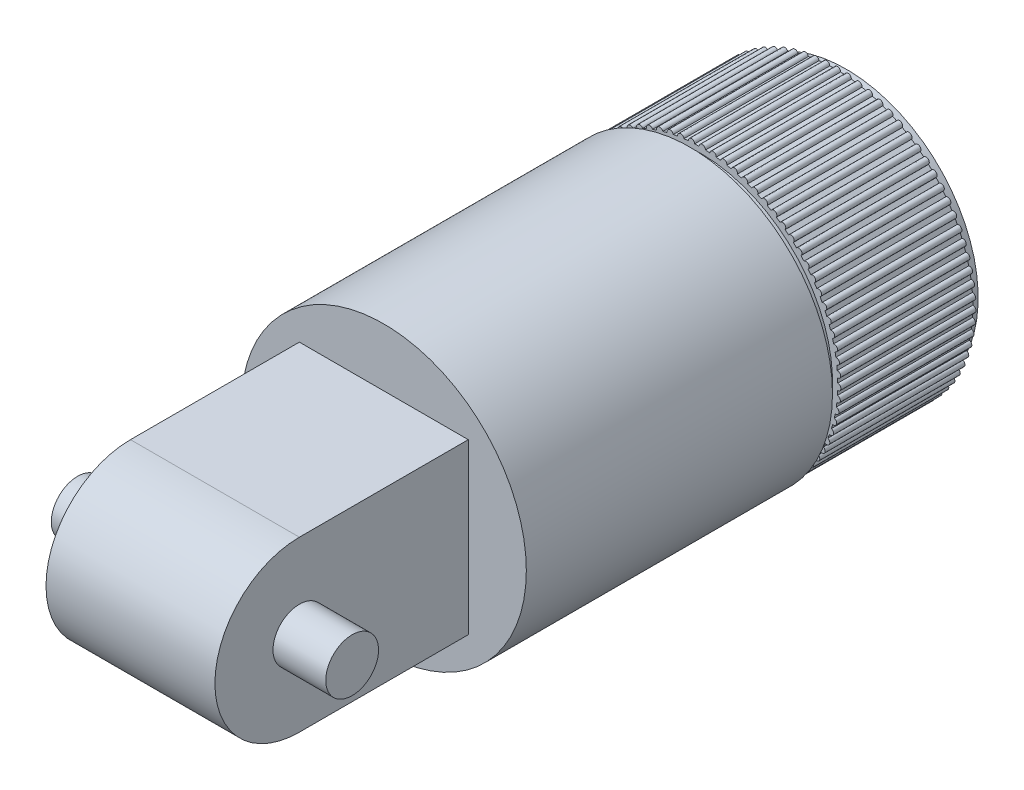
SolidWorks part; units mm, degrees
ref_plane "Front Plane" through (0, 0, 0) normal (0, 0, 1) x (1, 0, 0)
ref_plane "Top Plane" through (0, 0, 0) normal (0, 1, 0) x (1, 0, 0)
ref_plane "Right Plane" through (0, 0, 0) normal (1, 0, 0) x (0, 0, -1)
sketch "Sketch1" plane through (0, 0, 0) normal (0, 0, 1) x (1, 0, 0)
  circle A0 centre (0, 0) radius 3
  circle A1 centre (0, 0) radius 6.5
  arc A2 (0.2338, 6.4958) -> (-0.0661, 6.4997) centre (0.0839, 6.4995) ccw
  arc A3 (0.7428, 6.4574) -> (0.444, 6.4848) centre (0.5936, 6.4728) ccw
  arc A4 (1.2471, 6.3792) -> (0.9515, 6.43) centre (1.0996, 6.4063) ccw
  arc A5 (1.7438, 6.2617) -> (1.453, 6.3355) centre (1.5988, 6.3003) ccw
  arc A6 (2.2297, 6.1056) -> (1.9456, 6.202) centre (2.0882, 6.1554) ccw
  arc A7 (2.7019, 5.9118) -> (2.4262, 6.0302) centre (2.5647, 5.9726) ccw
  arc A8 (3.1574, 5.6816) -> (2.8919, 5.8213) centre (3.0254, 5.753) ccw
  arc A9 (3.5934, 5.4164) -> (3.3397, 5.5764) centre (3.4675, 5.4979) ccw
  arc A10 (4.0073, 5.1178) -> (3.7669, 5.2972) centre (3.8881, 5.2089) ccw
  arc A11 (4.3965, 4.7876) -> (4.1709, 4.9853) centre (4.2848, 4.8878) ccw
  arc A12 (4.7586, 4.4279) -> (4.5492, 4.6427) centre (4.6551, 4.5365) ccw
  arc A13 (5.0913, 4.0409) -> (4.8994, 4.2715) centre (4.9967, 4.1573) ccw
  arc A14 (5.3927, 3.629) -> (5.2195, 3.8739) centre (5.3075, 3.7524) ccw
  arc A15 (5.6608, 3.1947) -> (5.5073, 3.4524) centre (5.5855, 3.3244) ccw
  arc A16 (5.894, 2.7407) -> (5.7612, 3.0097) centre (5.8291, 2.876) ccw
  arc A17 (6.0908, 2.2698) -> (5.9796, 2.5484) centre (6.0368, 2.4097) ccw
  arc A18 (6.2501, 1.7849) -> (6.1611, 2.0714) centre (6.2073, 1.9287) ccw
  arc A19 (6.3709, 1.289) -> (6.3046, 1.5816) centre (6.3395, 1.4357) ccw
  arc A20 (6.4524, 0.7852) -> (6.4093, 1.0821) centre (6.4326, 0.9339) ccw
  arc A21 (6.4941, 0.2765) -> (6.4744, 0.5759) centre (6.486, 0.4263) ccw
  arc A22 (6.4958, -0.2338) -> (6.4997, 0.0661) centre (6.4995, -0.0839) ccw
  arc A23 (6.4574, -0.7428) -> (6.4848, -0.444) centre (6.4728, -0.5936) ccw
  arc A24 (6.3792, -1.2471) -> (6.43, -0.9515) centre (6.4063, -1.0996) ccw
  arc A25 (6.2617, -1.7438) -> (6.3355, -1.453) centre (6.3003, -1.5988) ccw
  arc A26 (6.1056, -2.2297) -> (6.202, -1.9456) centre (6.1554, -2.0882) ccw
  arc A27 (5.9118, -2.7019) -> (6.0302, -2.4262) centre (5.9726, -2.5647) ccw
  arc A28 (5.6816, -3.1574) -> (5.8213, -2.8919) centre (5.753, -3.0254) ccw
  arc A29 (5.4164, -3.5934) -> (5.5764, -3.3397) centre (5.4979, -3.4675) ccw
  arc A30 (5.1178, -4.0073) -> (5.2972, -3.7669) centre (5.2089, -3.8881) ccw
  arc A31 (4.7876, -4.3965) -> (4.9853, -4.1709) centre (4.8878, -4.2848) ccw
  arc A32 (4.4279, -4.7586) -> (4.6427, -4.5492) centre (4.5365, -4.6551) ccw
  arc A33 (4.0409, -5.0913) -> (4.2715, -4.8994) centre (4.1573, -4.9967) ccw
  arc A34 (3.629, -5.3927) -> (3.8739, -5.2195) centre (3.7524, -5.3075) ccw
  arc A35 (3.1947, -5.6608) -> (3.4524, -5.5073) centre (3.3244, -5.5855) ccw
  arc A36 (2.7407, -5.894) -> (3.0097, -5.7612) centre (2.876, -5.8291) ccw
  arc A37 (2.2698, -6.0908) -> (2.5484, -5.9796) centre (2.4097, -6.0368) ccw
  arc A38 (1.7849, -6.2501) -> (2.0714, -6.1611) centre (1.9287, -6.2073) ccw
  arc A39 (1.289, -6.3709) -> (1.5816, -6.3046) centre (1.4357, -6.3395) ccw
  arc A40 (0.7852, -6.4524) -> (1.0821, -6.4093) centre (0.9339, -6.4326) ccw
  arc A41 (0.2765, -6.4941) -> (0.5759, -6.4744) centre (0.4263, -6.486) ccw
  arc A42 (-0.2338, -6.4958) -> (0.0661, -6.4997) centre (-0.0839, -6.4995) ccw
  arc A43 (-0.7428, -6.4574) -> (-0.444, -6.4848) centre (-0.5936, -6.4728) ccw
  arc A44 (-1.2471, -6.3792) -> (-0.9515, -6.43) centre (-1.0996, -6.4063) ccw
  arc A45 (-1.7438, -6.2617) -> (-1.453, -6.3355) centre (-1.5988, -6.3003) ccw
  arc A46 (-2.2297, -6.1056) -> (-1.9456, -6.202) centre (-2.0882, -6.1554) ccw
  arc A47 (-2.7019, -5.9118) -> (-2.4262, -6.0302) centre (-2.5647, -5.9726) ccw
  arc A48 (-3.1574, -5.6816) -> (-2.8919, -5.8213) centre (-3.0254, -5.753) ccw
  arc A49 (-3.5934, -5.4164) -> (-3.3397, -5.5764) centre (-3.4675, -5.4979) ccw
  arc A50 (-4.0073, -5.1178) -> (-3.7669, -5.2972) centre (-3.8881, -5.2089) ccw
  arc A51 (-4.3965, -4.7876) -> (-4.1709, -4.9853) centre (-4.2848, -4.8878) ccw
  arc A52 (-4.7586, -4.4279) -> (-4.5492, -4.6427) centre (-4.6551, -4.5365) ccw
  arc A53 (-5.0913, -4.0409) -> (-4.8994, -4.2715) centre (-4.9967, -4.1573) ccw
  arc A54 (-5.3927, -3.629) -> (-5.2195, -3.8739) centre (-5.3075, -3.7524) ccw
  arc A55 (-5.6608, -3.1947) -> (-5.5073, -3.4524) centre (-5.5855, -3.3244) ccw
  arc A56 (-5.894, -2.7407) -> (-5.7612, -3.0097) centre (-5.8291, -2.876) ccw
  arc A57 (-6.0908, -2.2698) -> (-5.9796, -2.5484) centre (-6.0368, -2.4097) ccw
  arc A58 (-6.2501, -1.7849) -> (-6.1611, -2.0714) centre (-6.2073, -1.9287) ccw
  arc A59 (-6.3709, -1.289) -> (-6.3046, -1.5816) centre (-6.3395, -1.4357) ccw
  arc A60 (-6.4524, -0.7852) -> (-6.4093, -1.0821) centre (-6.4326, -0.9339) ccw
  arc A61 (-6.4941, -0.2765) -> (-6.4744, -0.5759) centre (-6.486, -0.4263) ccw
  arc A62 (-6.4958, 0.2338) -> (-6.4997, -0.0661) centre (-6.4995, 0.0839) ccw
  arc A63 (-6.4574, 0.7428) -> (-6.4848, 0.444) centre (-6.4728, 0.5936) ccw
  arc A64 (-6.3792, 1.2471) -> (-6.43, 0.9515) centre (-6.4063, 1.0996) ccw
  arc A65 (-6.2617, 1.7438) -> (-6.3355, 1.453) centre (-6.3003, 1.5988) ccw
  arc A66 (-6.1056, 2.2297) -> (-6.202, 1.9456) centre (-6.1554, 2.0882) ccw
  arc A67 (-5.9118, 2.7019) -> (-6.0302, 2.4262) centre (-5.9726, 2.5647) ccw
  arc A68 (-5.6816, 3.1574) -> (-5.8213, 2.8919) centre (-5.753, 3.0254) ccw
  arc A69 (-5.4164, 3.5934) -> (-5.5764, 3.3397) centre (-5.4979, 3.4675) ccw
  arc A70 (-5.1178, 4.0073) -> (-5.2972, 3.7669) centre (-5.2089, 3.8881) ccw
  arc A71 (-4.7876, 4.3965) -> (-4.9853, 4.1709) centre (-4.8878, 4.2848) ccw
  arc A72 (-4.4279, 4.7586) -> (-4.6427, 4.5492) centre (-4.5365, 4.6551) ccw
  arc A73 (-4.0409, 5.0913) -> (-4.2715, 4.8994) centre (-4.1573, 4.9967) ccw
  arc A74 (-3.629, 5.3927) -> (-3.8739, 5.2195) centre (-3.7524, 5.3075) ccw
  arc A75 (-3.1947, 5.6608) -> (-3.4524, 5.5073) centre (-3.3244, 5.5855) ccw
  arc A76 (-2.7407, 5.894) -> (-3.0097, 5.7612) centre (-2.876, 5.8291) ccw
  arc A77 (-2.2698, 6.0908) -> (-2.5484, 5.9796) centre (-2.4097, 6.0368) ccw
  arc A78 (-1.7849, 6.2501) -> (-2.0714, 6.1611) centre (-1.9287, 6.2073) ccw
  arc A79 (-1.289, 6.3709) -> (-1.5816, 6.3046) centre (-1.4357, 6.3395) ccw
  arc A80 (-0.7852, 6.4524) -> (-1.0821, 6.4093) centre (-0.9339, 6.4326) ccw
  arc A81 (-0.2765, 6.4941) -> (-0.5759, 6.4744) centre (-0.4263, 6.486) ccw
  point P5 (0, 0)
  point P8 (0, 0)
  dimension "D1" = 6
  dimension "D2" = 13
  dimension "D3" = 0.3
  dimension "D4" = 80
extrude "Boss-Extrude1" add sketch "Sketch1" along normal blind 6.4 contours A1 | A1 A77 | A1 A76 | A1 A75 | A1 A74 | A1 A73 | A1 A72 | A1 A71 | A1 A70 | A1 A69 | A1 A68 | A1 A67 | A1 A66 | A1 A65 | A1 A64 | A1 A63 | A1 A62 | A1 A61 | A1 A60 | A1 A59 | A1 A58 | A1 A57 | A1 A56 | A1 A55 | A1 A54 | A1 A53 | A1 A52 | A1 A51 | A1 A49 | A1 A50 | A1 A48 | A1 A47 | A1 A46 | A1 A44 | A1 A45 | A1 A43 | A1 A42 | A1 A41 | A1 A40 | A1 A39 | A1 A38 | A1 A37 | A1 A36 | A1 A35 | A1 A34 | A1 A33 | A1 A32 | A1 A31 | A1 A30 | A1 A29 | A1 A28 | A1 A27 | A1 A26 | A1 A25 | A1 A24 | A1 A23 | A1 A22 | A1 A21 | A1 A20 | A1 A19 | A1 A18 | A1 A17 | A1 A16 | A1 A15 | A1 A14 | A1 A13 | A1 A12 | A1 A11 | A1 A10 | A1 A9 | A1 A8 | A1 A7 | A1 A6 | A1 A5 | A1 A4 | A1 A3 | A1 A2 | A1 A81 | A1 A80 | A1 A79 | A1 A78
sketch "Sketch2" plane through (0, 0, 0) normal (0, 0, -1) x (-1, 0, 0)
  circle A0 centre (0, 0) radius 3 construction
  circle A1 centre (0, 0) radius 3
  circle A2 centre (0, 0) radius 6.25
  dimension "D1" = 12.5
extrude "Boss-Extrude2" add sketch "Sketch2" along normal blind 0.5 and the other way blind 6.9
sketch "Sketch4" plane through (0, 0, 6.9) normal (0, 0, 1) x (1, 0, 0)
  circle A0 centre (0, 0) radius 6.75
  dimension "D1" = 13.5
extrude "Boss-Extrude4" add sketch "Sketch4" along normal blind 14.5
sketch "Sketch5" plane through (0, 0, 21.4) normal (0, 0, 1) x (1, 0, 0)
  line L1 (4, -4) -> (-4, -4)
  line L2 (4, -4) -> (4, 4)
  line L3 (4, 4) -> (-4, 4)
  line L4 (-4, -4) -> (-4, 4)
  line L5 (4, -4) -> (-4, 4) construction
  line L6 (4, 4) -> (-4, -4) construction
  point P0 (0, 0)
  dimension "D1" = 8
  dimension "D2" = 8
extrude "Boss-Extrude5" add sketch "Sketch5" along normal blind 8
sketch "Sketch6" plane through (-4, 0, 0) normal (-1, 0, 0) x (0, 0, 1)
  line L0 (29.4, 4) -> (29.4, -4) construction
  line L1 (29.4, 4) -> (29.4, -4)
  arc A0 (29.4, -4) -> (29.4, 4) centre (29.4, 0) ccw
extrude "Boss-Extrude6" add sketch "Sketch6" against normal blind 8
sketch "Sketch8" plane through (0, 0, 0) normal (1, 0, 0) x (0, 0, -1)
  arc A0 (-29.4, 4) -> (-29.4, -4) centre (-29.4, 0) ccw construction
  arc A1 (-29.4, 4) -> (-29.4, -4) centre (-29.4, 0) ccw
  circle A2 centre (-29.4, 0) radius 1.25
  dimension "D1" = 2.5
extrude "Boss-Extrude7" add sketch "Sketch8" along normal blind 6.5 and the other way blind 6.5 contours A2
